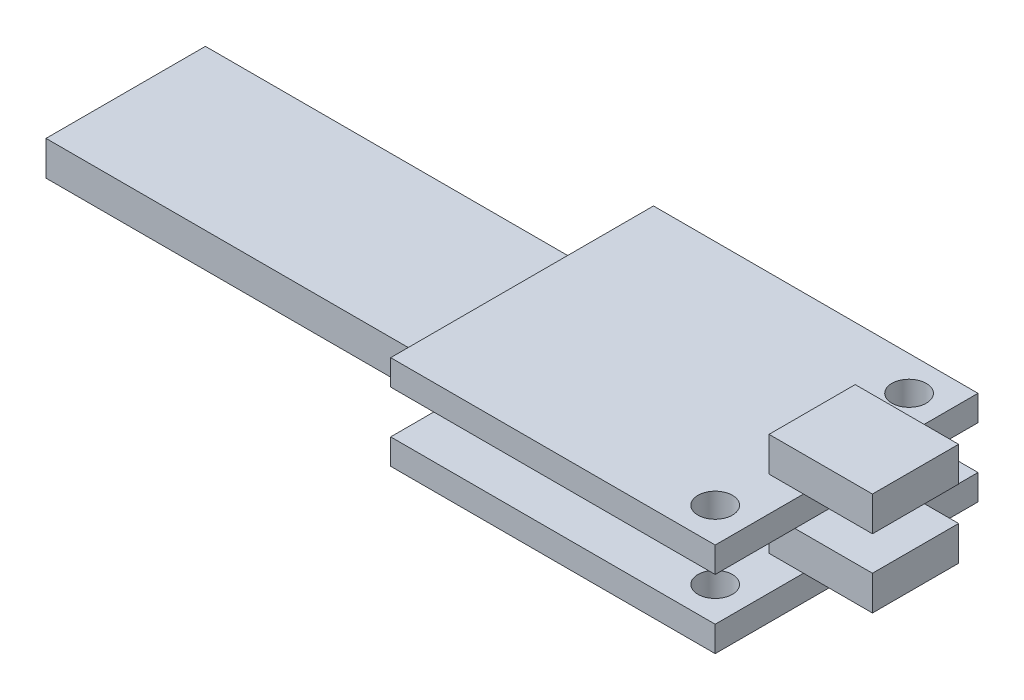
SolidWorks part; units mm, degrees
ref_plane "Front Plane" through (0, 0, 0) normal (0, 0, 1) x (1, 0, 0)
ref_plane "Top Plane" through (0, 0, 0) normal (0, 1, 0) x (1, 0, 0)
ref_plane "Right Plane" through (0, 0, 0) normal (1, 0, 0) x (0, 0, -1)
sketch "Sketch1" plane through (0, 0, 0) normal (0, 1, 0) x (1, 0, 0)
  line L1 (0, 0) -> (18.83, 0)
  line L2 (0, 0) -> (0, 15.25)
  line L3 (0, 15.25) -> (18.83, 15.25)
  line L4 (18.83, 0) -> (18.83, 15.25)
  circle A0 centre (16.83, 13.25) radius 1
  circle A1 centre (16.83, 2) radius 1
  dimension "D3" = 2
  dimension "D4" = 2
  dimension "D5" = 2
  dimension "D6" = 2
  dimension "D7" = 2
  dimension "D8" = 2
  dimension "D1" = 18.83
  dimension "D2" = 15.25
extrude "Boss-Extrude1" add sketch "Sketch1" along normal blind 1.48
sketch "Sketch2" plane through (0, 1.48, 0) normal (0, 1, 0) x (1, 0, 0)
  line L0 (18.83, 0) -> (18.83, 15.25) construction
  line L1 (16.83, 10.125) -> (22.83, 10.125)
  line L2 (16.83, 10.125) -> (16.83, 5.125)
  line L3 (16.83, 5.125) -> (22.83, 5.125)
  line L4 (22.83, 10.125) -> (22.83, 5.125)
  line L5 (0, 0) -> (18.83, 0) construction
  line L6 (18.83, 15.25) -> (0, 15.25) construction
  dimension "D1" = 4
  dimension "D2" = 5
  dimension "D3" = 5.125
  dimension "D4" = 5.125
  dimension "D5" = 2
extrude "Boss-Extrude2" add sketch "Sketch2" along normal blind 2
sketch "Sketch3" plane through (0, 1.48, 0) normal (0, 1, 0) x (1, 0, 0)
  line L0 (18.83, 15.25) -> (0, 15.25) construction
  line L1 (0, 0) -> (18.83, 0) construction
  line L2 (0, 15.25) -> (0, 0) construction
  line L3 (18.83, 10.125) -> (18.83, 15.25) construction
  circle A0 centre (9.415, 7.625) radius 0.9017
  dimension "D1" = 7.625
  dimension "D2" = 7.625
  dimension "D3" = 9.415
  dimension "D4" = 9.415
extrude "Boss-Extrude3" add sketch "Sketch3" along normal blind 2.5
sketch "Sketch4" plane through (0, 3.98, 0) normal (0, 1, 0) x (1, 0, 0)
  line L2 (18.83, 5.125) -> (18.83, 10.125)
  line L8 (16.83, 10.125) -> (18.83, 10.125)
  line L9 (18.83, 10.125) -> (18.83, 15.25)
  line L10 (18.83, 15.25) -> (0, 15.25)
  line L11 (0, 15.25) -> (0, 0)
  line L12 (0, 0) -> (18.83, 0)
  line L13 (18.83, 0) -> (18.83, 5.125)
  line L14 (18.83, 5.125) -> (16.83, 5.125)
  line L15 (16.83, 5.125) -> (16.83, 10.125)
  line L16 (16.83, 10.125) -> (18.83, 10.125)
  line L17 (18.83, 10.125) -> (18.83, 15.25)
  line L18 (18.83, 15.25) -> (0, 15.25)
  line L19 (0, 15.25) -> (0, 0)
  line L20 (0, 0) -> (18.83, 0)
  line L21 (18.83, 0) -> (18.83, 5.125)
  line L22 (18.83, 5.125) -> (16.83, 5.125)
  line L23 (16.83, 5.125) -> (16.83, 10.125)
  circle A0 centre (16.83, 13.25) radius 1 construction
  circle A1 centre (16.83, 2) radius 1 construction
  circle A2 centre (16.83, 13.25) radius 1
  circle A3 centre (16.83, 2) radius 1
  circle M9 centre (9.415, 7.625) radius 0.9017
  dimension "D1" = 0
extrude "Boss-Extrude4" add sketch "Sketch4" along normal blind 1.48 separate body contours L23 L22 L2 L16 | L22 L23 L16 L17 L18 L19 L20 L21 M9 | M9
sketch "Sketch5" plane through (0, 5.46, 0) normal (0, 1, 0) x (1, 0, 0)
  line L4 (16.83, 10.125) -> (16.83, 5.125)
  line L5 (16.83, 5.125) -> (22.83, 5.125)
  line L6 (22.83, 5.125) -> (22.83, 10.125)
  line L7 (22.83, 10.125) -> (16.83, 10.125)
  line L8 (16.83, 10.125) -> (16.83, 5.125)
  line L9 (16.83, 5.125) -> (22.83, 5.125)
  line L10 (22.83, 5.125) -> (22.83, 10.125)
  line L11 (22.83, 10.125) -> (16.83, 10.125)
  dimension "D1" = 0
extrude "Boss-Extrude5" add sketch "Sketch5" along normal blind 2
sketch "Sketch6" plane through (0, 1.48, 0) normal (0, 1, 0) x (1, 0, 0)
  line L0 (0, 15.25) -> (0, 0) construction
  line L1 (0, 12.25) -> (2, 12.25)
  line L2 (0, 12.25) -> (0, 3)
  line L3 (0, 3) -> (2, 3)
  line L4 (2, 12.25) -> (2, 3)
  line L5 (18.83, 15.25) -> (0, 15.25) construction
  line L6 (0, 0) -> (18.83, 0) construction
  dimension "D1" = 2
  dimension "D2" = 3
  dimension "D3" = 3
extrude "Boss-Extrude6" add sketch "Sketch6" along normal blind 2
sketch "Sketch7" plane through (0, 0, 0) normal (-1, 0, 0) x (0, 0, 1)
  line L1 (-3, 3.48) -> (-12.25, 3.48)
  line L2 (-3, 3.48) -> (-3, 1.48)
  line L3 (-3, 1.48) -> (-12.25, 1.48)
  line L4 (-12.25, 3.48) -> (-12.25, 1.48)
extrude "Boss-Extrude7" add sketch "Sketch7" along normal blind 23
sketch "Sketch8" plane through (0, 7.46, 0) normal (0, 1, 0) x (1, 0, 0)
  line L0 (16.83, 7.625) -> (22.83, 7.625)
  line L1 (16.83, 5.125) -> (22.83, 5.125)
  line L2 (16.83, 5.125) -> (16.83, 10.125)
  line L3 (16.83, 10.125) -> (22.83, 10.125)
  line L4 (22.83, 5.125) -> (22.83, 10.125)
  line L5 (19.83, 10.125) -> (19.83, 5.125)
  circle A0 centre (19.83, 7.625) radius 1.5
  dimension "D1" = 3
sketch "Sketch9" plane through (0, 0, 0) normal (0, -1, 0) x (1, 0, 0)
  line L0 (0, 0) -> (18.83, 0) construction
  line L1 (18.83, -15.25) -> (0, -15.25) construction
  line L2 (18.83, 0) -> (18.83, -15.25) construction
  circle A0 centre (8.83, -7.625) radius 1.5
  dimension "D1" = 3
  dimension "D2" = 7.625
  dimension "D3" = 7.625
  dimension "D4" = 10
extrude "Boss-Extrude8" add sketch "Sketch9" along normal blind 2
